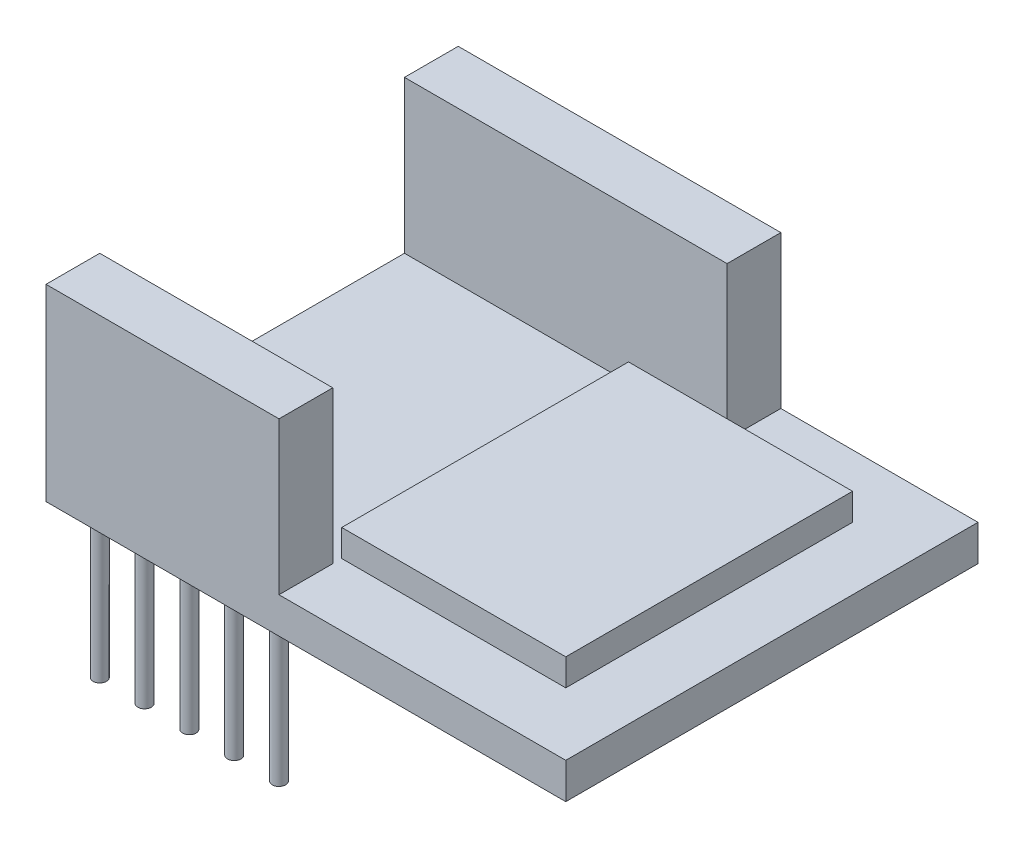
SolidWorks part; units mm, degrees
ref_plane "Front Plane" through (0, 0, 0) normal (0, 0, 1) x (1, 0, 0)
ref_plane "Top Plane" through (0, 0, 0) normal (0, 1, 0) x (1, 0, 0)
ref_plane "Right Plane" through (0, 0, 0) normal (1, 0, 0) x (0, 0, -1)
sketch "Sketch1" plane through (0, 0, 0) normal (0, 1, 0) x (1, 0, 0)
  line L1 (-14.5, 11.5) -> (14.5, 11.5)
  line L2 (-14.5, 11.5) -> (-14.5, -11.5)
  line L3 (-14.5, -11.5) -> (14.5, -11.5)
  line L4 (14.5, 11.5) -> (14.5, -11.5)
  line L5 (-14.5, 11.5) -> (14.5, -11.5) construction
  line L6 (-14.5, -11.5) -> (14.5, 11.5) construction
  point P0 (0, 0)
  dimension "D1" = 23
  dimension "D2" = 29
extrude "Boss-Extrude1" add sketch "Sketch1" along normal blind 2
sketch "Sketch2" plane through (0, 2, 0) normal (0, 1, 0) x (1, 0, 0)
  line L0 (-14.5, 0) -> (14.5, 0) construction
  line L1 (-14.5, -11.5) -> (-1.5, -11.5)
  line L2 (-14.5, -11.5) -> (-14.5, -8.5)
  line L3 (-14.5, -8.5) -> (-1.5, -8.5)
  line L4 (-1.5, -11.5) -> (-1.5, -8.5)
  line L5 (-14.5, 11.5) -> (-14.5, -11.5) construction
  line L6 (14.5, -11.5) -> (14.5, 11.5) construction
  line L7 (-14.5, 11.5) -> (-14.5, 8.5)
  line L8 (-14.5, 11.5) -> (3.5, 11.5)
  line L9 (3.5, 11.5) -> (3.5, 8.5)
  line L10 (-14.5, 8.5) -> (3.5, 8.5)
  dimension "D1" = 13
  dimension "D2" = 3
  dimension "D3" = 3
  dimension "D4" = 18
extrude "Boss-Extrude2" add sketch "Sketch2" along normal blind 8.5
sketch "Sketch3" plane through (0, 0, 0) normal (0, -1, 0) x (1, 0, 0)
  line L0 (-14.5, -8.5) -> (3.5, -8.5) construction
  line L1 (-14.5, -11.5) -> (-14.5, 11.5) construction
  line L2 (3.5, -8.5) -> (3.5, -11.5) construction
  line L3 (14.5, -11.5) -> (-14.5, -11.5) construction
  line L4 (3.5, -10) -> (-14.5, -10) construction
  line L5 (-14.5, 0) -> (14.5, 0) construction
  line L6 (14.5, 11.5) -> (14.5, -11.5) construction
  circle A0 centre (2, -10) radius 0.375
  circle A1 centre (-0.5, -10) radius 0.375
  circle A2 centre (-3, -10) radius 0.375
  circle A3 centre (-5.5, -10) radius 0.375
  circle A4 centre (-8, -10) radius 0.375
  circle A5 centre (-3, 10) radius 0.375
  circle A6 centre (-5.5, 10) radius 0.375
  circle A7 centre (-8, 10) radius 0.375
  circle A8 centre (-10.5, 10) radius 0.375
  circle A9 centre (-13, 10) radius 0.375
  circle A10 centre (-10.5, -10) radius 0.375
  circle A11 centre (-13, -10) radius 0.375
  dimension "D3" = 0.75
  dimension "D4" = 1.5
  dimension "D6" = 4
  dimension "D7" = 1.5
  dimension "D1" = 18
  dimension "D2" = 3
  dimension "D5" = 7
extrude "Boss-Extrude3" add sketch "Sketch3" along normal blind 8.5
sketch "Sketch5" plane through (0, 2, 0) normal (0, 1, 0) x (1, 0, 0)
  line L22 (11, 8) -> (-1.5, 8)
  line L23 (-1.5, 8) -> (-1.5, -8)
  line L25 (-1.5, -8) -> (11, -8)
  line L26 (11, -8) -> (11, 8)
  line L27 (11, 8) -> (3.5, 8)
  line L28 (-1.5, -8) -> (11, -8)
  line L29 (11, -8) -> (11, 8)
  dimension "D1" = 3.5
extrude "Boss-Extrude4" add sketch "Sketch5" along normal blind 1.5
